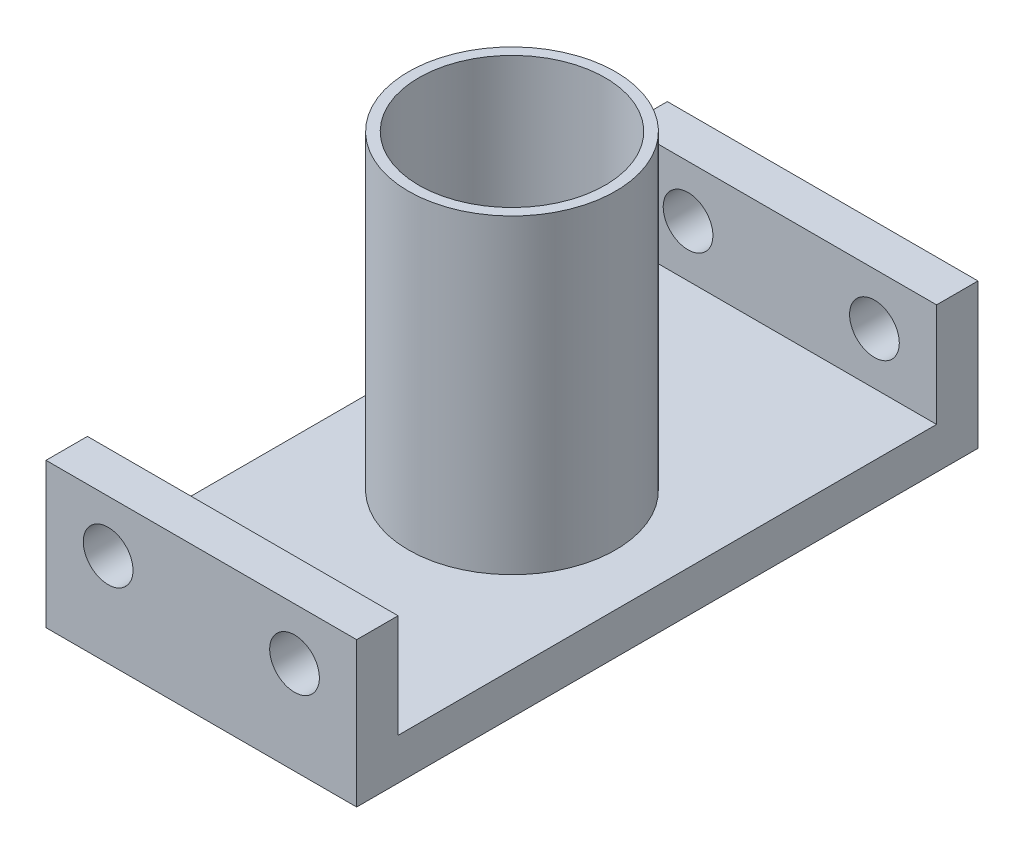
SolidWorks part; units mm, degrees
ref_plane "Plan de face" through (0, 0, 0) normal (0, 0, 1) x (1, 0, 0)
ref_plane "Plan de dessus" through (0, 0, 0) normal (0, 1, 0) x (1, 0, 0)
ref_plane "Plan de droite" through (0, 0, 0) normal (1, 0, 0) x (0, 0, -1)
sketch "Esquisse1" plane through (0, 0, 0) normal (0, 1, 0) x (1, 0, 0)
  line L1 (-9.3855, 48.0984) -> (5.6145, 48.0984)
  line L2 (-9.3855, 48.0984) -> (-9.3855, 18.0984)
  line L3 (-9.3855, 18.0984) -> (5.6145, 18.0984)
  line L4 (5.6145, 48.0984) -> (5.6145, 18.0984)
  dimension "D1" = 30
  dimension "D2" = 15
extrude "Boss.-Extru.1" add sketch "Esquisse1" along normal blind 2
sketch "Esquisse4" plane through (0, 2, 0) normal (0, 1, 0) x (1, 0, 0)
  line L0 (5.6145, 18.0984) -> (5.6145, 48.0984) construction
  line L1 (-9.3855, 48.0984) -> (5.6145, 48.0984)
  line L2 (-9.3855, 48.0984) -> (-9.3855, 46.0984)
  line L3 (-9.3855, 46.0984) -> (5.6145, 46.0984)
  line L4 (5.6145, 48.0984) -> (5.6145, 46.0984)
  line L6 (-9.3855, 18.0984) -> (5.6145, 18.0984)
  line L7 (-9.3855, 18.0984) -> (-9.3855, 20.0984)
  line L8 (-9.3855, 20.0984) -> (5.6145, 20.0984)
  line L9 (5.6145, 18.0984) -> (5.6145, 20.0984)
  dimension "D1" = 2
  dimension "D2" = 2
extrude "Boss.-Extru.3" add sketch "Esquisse4" along normal blind 5
hole_wizard "Dégagement M21" positions "Esquisse6" profile "Esquisse5" hole size "M2" standard "Din" end condition through all
sketch "Esquisse6" plane through (0, 0, -18.0984) normal (0, 0, 1) x (1, 0, 0)
  line L0 (-9.3855, 4.5) -> (5.6145, 4.5) construction
  line L1 (-9.3855, 7) -> (-9.3855, 0) construction
  line L3 (5.6145, 7) -> (5.6145, 0) construction
  line L5 (-9.3855, 7) -> (5.6145, 7) construction
  point P0 (-6.3855, 4.5)
  point P2 (2.6145, 4.5)
  dimension "D1" = 2.5
  dimension "D2" = 3
  dimension "D3" = 3
sketch "Esquisse5" plane through (-6.3855, 4.5, -18.0984) normal (1, 0, 0) x (0, -1, 0)
  line L0 (0, 0) -> (0, 30)
  line L1 (0, 30) -> (1.2, 30)
  line L2 (1.2, 30) -> (1.2, 0)
  line L5 (1.2, 0) -> (0, 0)
  line L11 (0, -6.35) -> (0, 107.95) construction
  dimension "Diamètre du perçage jusqu'au prochain" = 2.4
  dimension "Profondeur du perçage jusqu'au prochain" = 30
sketch "Esquisse2" plane through (0, 2, 0) normal (0, 1, 0) x (1, 0, 0)
  line L0 (-9.3855, 33.0984) -> (5.6145, 33.0984) construction
  line L1 (-9.3855, 46.0984) -> (-9.3855, 20.0984) construction
  line L2 (5.6145, 20.0984) -> (5.6145, 46.0984) construction
  circle A0 centre (-1.8855, 33.0984) radius 5
  dimension "D1" = 10
extrude "Boss.-Extru.2" add sketch "Esquisse2" along normal blind 15
sketch "Esquisse3" plane through (0, 17, 0) normal (0, 1, 0) x (1, 0, 0)
  circle A0 centre (-1.8855, 33.0984) radius 4.5
  circle A1 centre (-1.8855, 33.0984) radius 5 construction
  dimension "D1" = 9
extrude "Enlèv. mat.-Extru.3" cut sketch "Esquisse3" against normal through all contours A0
